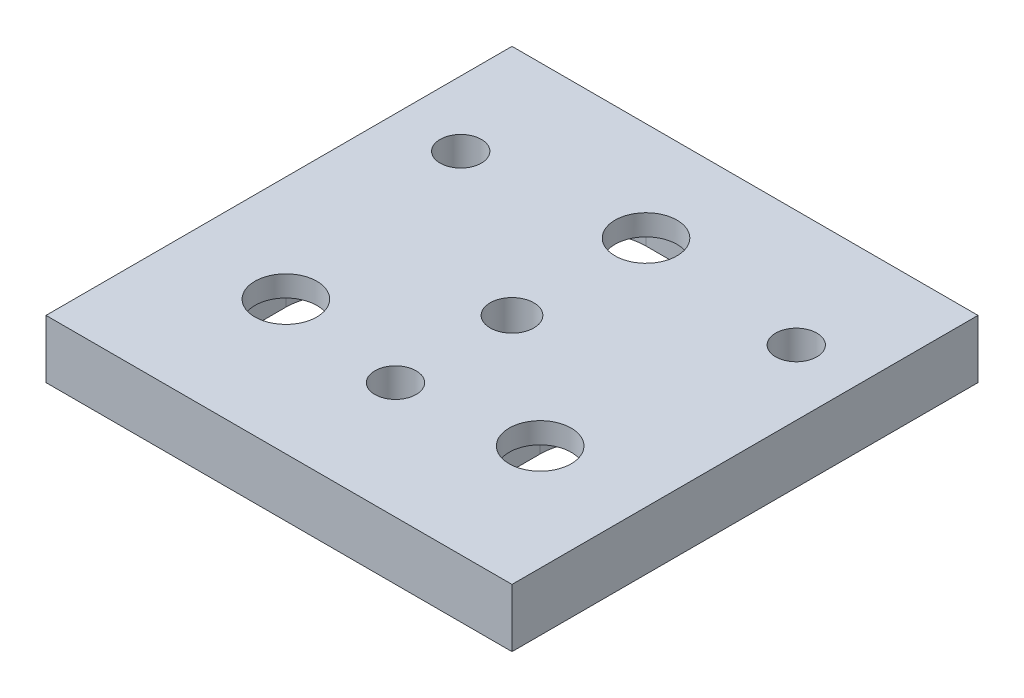
SolidWorks part; units mm, degrees
material "Copper"
ref_plane "Front Plane" through (0, 0, 0) normal (0, 0, 1) x (1, 0, 0)
ref_plane "Top Plane" through (0, 0, 0) normal (0, 1, 0) x (1, 0, 0)
ref_plane "Right Plane" through (0, 0, 0) normal (1, 0, 0) x (0, 0, -1)
sketch "Sketch1" plane through (0, 0, 0) normal (0, 1, 0) x (1, 0, 0)
  line L1 (-25.4, 25.4) -> (25.4, 25.4)
  line L2 (-25.4, 25.4) -> (-25.4, -25.4)
  line L3 (-25.4, -25.4) -> (25.4, -25.4)
  line L4 (25.4, 25.4) -> (25.4, -25.4)
  dimension "D1" = 50.8
  dimension "D2" = 50.8
  dimension "D3" = 25.4
  dimension "D4" = 25.4
extrude "Boss-Extrude1" add sketch "Sketch1" along normal blind 6.35
hole_wizard "#8 Clearance Hole1" positions "Sketch5" profile "Sketch4" hole size "#8" standard "ANSI Inch" end condition through all
sketch "Sketch5" plane through (0, 6.35, 0) normal (0, 1, 0) x (1, 0, 0)
  line L1 (25.4, 25.4) -> (-25.4, 25.4) construction
  line L3 (-25.4, -25.4) -> (25.4, -25.4) construction
  point P0 (-18.288, 12.7)
  point P6 (18.288, 12.7)
  point P21 (0, -12.7)
  dimension "D1" = 12.7
  dimension "D2" = 12.7
  dimension "D3" = 18.288
  dimension "D4" = 18.288
sketch "Sketch4" plane through (-18.288, 6.35, -12.7) normal (1, 0, 0) x (0, 0, 1)
  line L0 (0, 0) -> (0, 6.35)
  line L1 (0, 6.35) -> (2.2479, 6.35)
  line L2 (2.2479, 6.35) -> (2.2479, 0)
  line L5 (2.2479, 0) -> (0, 0)
  line L11 (0, -6.35) -> (0, 107.95) construction
  dimension "Thru Hole Dia." = 4.4958
  dimension "Thru Hole Depth" = 6.35
hole_wizard "1/4 Clearance Hole1" positions "Sketch7" profile "Sketch6" hole size "1/4" standard "ANSI Inch" end condition through all
sketch "Sketch7" plane through (0, 6.35, 0) normal (0, 1, 0) x (1, 0, 0)
  point P0 (0, 14.6101)
  point P2 (-13.8608, -10.7899)
  point P4 (13.8608, -10.7899)
  dimension "D1" = 14.6101
  dimension "D2" = 10.7899
  dimension "D3" = 13.8608
  dimension "D4" = 27.7216
sketch "Sketch6" plane through (0, 6.35, -14.6101) normal (1, 0, 0) x (0, 0, 1)
  line L0 (0, 0) -> (0, 6.35)
  line L1 (0, 6.35) -> (3.3782, 6.35)
  line L2 (3.3782, 6.35) -> (3.3782, 0)
  line L5 (3.3782, 0) -> (0, 0)
  line L11 (0, -6.35) -> (0, 107.95) construction
  dimension "Thru Hole Dia." = 6.7564
  dimension "Thru Hole Depth" = 6.35
sketch "Sketch8" plane through (0, 0, 0) normal (0, -1, 0) x (1, 0, 0)
  line L2 (-19.4488, 16.3779) -> (-19.4488, 5.2019)
  line L4 (-8.2728, 16.3779) -> (-8.2728, 5.2019)
  line L6 (8.2728, 16.3779) -> (8.2728, 5.2019)
  line L8 (19.4488, 16.3779) -> (19.4488, 5.2019)
  line L9 (-5.588, -9.0221) -> (5.588, -9.0221)
  line L11 (-5.588, -20.1981) -> (5.588, -20.1981)
  circle A0 centre (-13.8608, 10.7899) radius 3.3782 construction
  circle A1 centre (13.8608, 10.7899) radius 3.3782 construction
  circle A2 centre (0, -14.6101) radius 3.3782 construction
  arc A3 (-19.4488, 16.3779) -> (-8.2728, 16.3779) centre (-13.8608, 16.3779) cw
  arc A4 (-19.4488, 5.2019) -> (-8.2728, 5.2019) centre (-13.8608, 5.2019) ccw
  arc A5 (8.2728, 16.3779) -> (19.4488, 16.3779) centre (13.8608, 16.3779) cw
  arc A6 (19.4488, 5.2019) -> (8.2728, 5.2019) centre (13.8608, 5.2019) cw
  arc A7 (-5.588, -9.0221) -> (-5.588, -20.1981) centre (-5.588, -14.6101) ccw
  arc A8 (5.588, -9.0221) -> (5.588, -20.1981) centre (5.588, -14.6101) cw
  dimension "D1" = 11.176
  dimension "D2" = 5.588
  dimension "D3" = 5.588
  dimension "D5" = 11.176
  dimension "D6" = 5.588
  dimension "D7" = 5.588
  dimension "D8" = 5.588
extrude "Cut-Extrude1" cut sketch "Sketch8" against normal blind 4.064
sketch "Sketch9" plane through (0, 6.35, 0) normal (0, 1, 0) x (1, 0, 0)
  circle A0 centre (0, 0) radius 2.3813
  dimension "D1" = 4.7625
extrude "Cut-Extrude2" cut sketch "Sketch9" against normal through all
